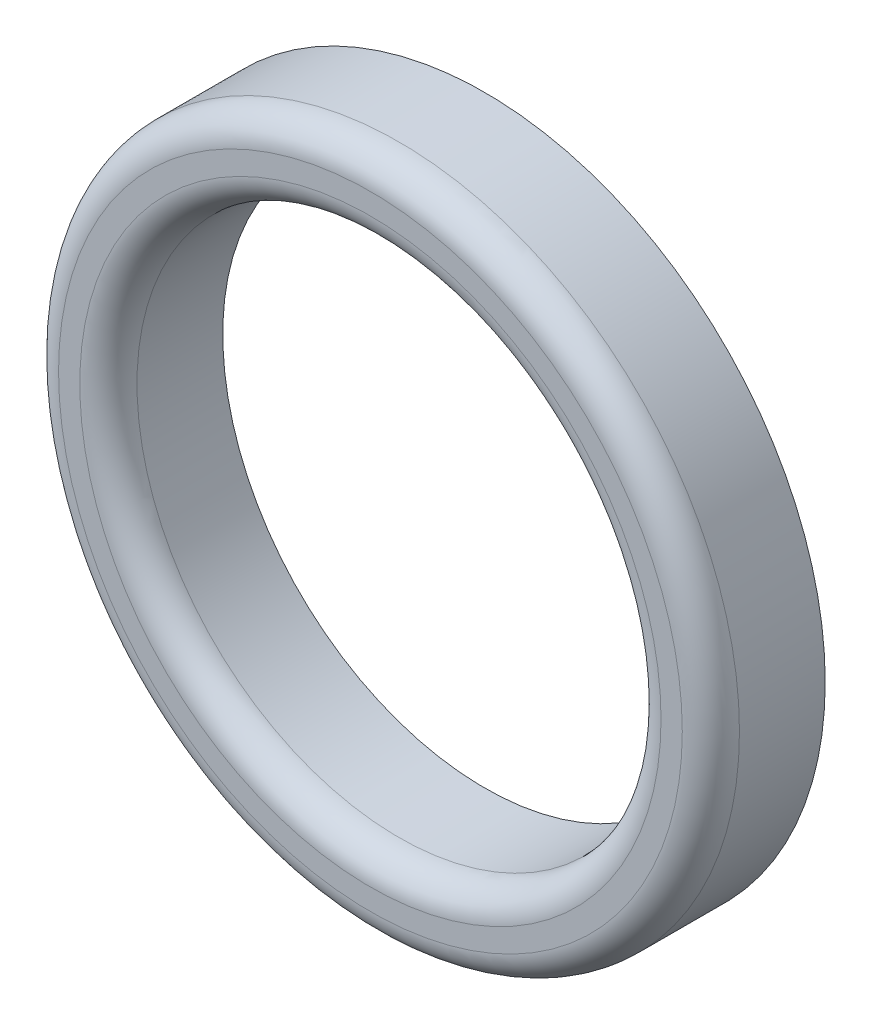
SolidWorks part; units mm, degrees
material "moto_glass_red"
ref_plane "Front Plane" through (0, 0, 0) normal (0, 0, 1) x (1, 0, 0)
ref_plane "Top Plane" through (0, 0, 0) normal (0, 1, 0) x (1, 0, 0)
ref_plane "Right Plane" through (0, 0, 0) normal (1, 0, 0) x (0, 0, -1)
sketch "Sketch1" plane through (0, 0, 0) normal (0, 0, 1) x (1, 0, 0)
  circle A0 centre (0, 0) radius 35.73
  circle A1 centre (0, 0) radius 27.5
  dimension "D1" = 71.46
  dimension "D2" = 55
extrude "Boss-Extrude1" add sketch "Sketch1" along normal blind 12
fillet "Fillet1" radius 3 2 edges at (35.73, 0, 12) (27.5, 0, 12)
shell "Shell1" thickness 1
